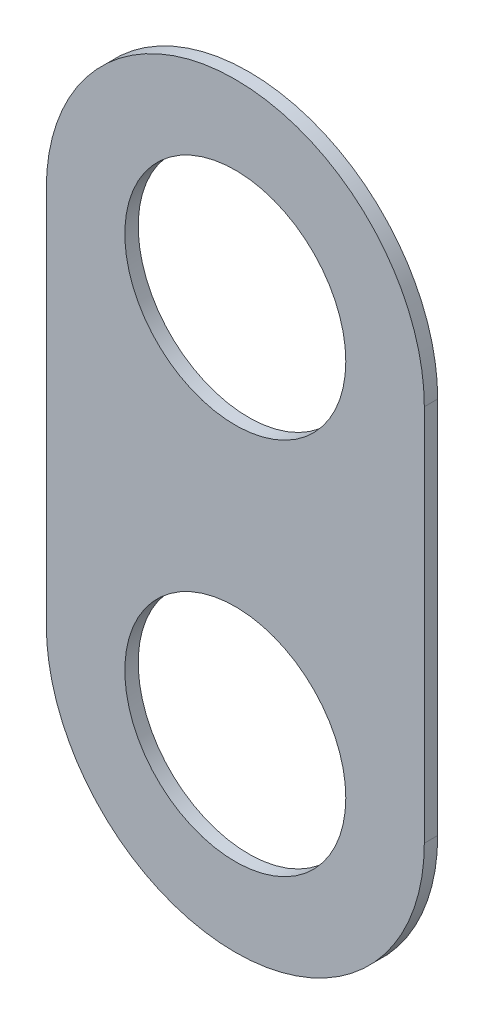
SolidWorks part; units mm, degrees
material "ASTM A36 Steel"
ref_plane "Front Plane" through (0, 0, 0) normal (0, 0, 1) x (1, 0, 0)
ref_plane "Top Plane" through (0, 0, 0) normal (0, 1, 0) x (1, 0, 0)
ref_plane "Right Plane" through (0, 0, 0) normal (1, 0, 0) x (0, 0, -1)
sketch "Sketch1" plane through (0, 0, 0) normal (0, 0, 1) x (1, 0, 0)
  line L0 (0, 24.7987) -> (0, -13.3013)
  line L1 (38.1, 24.7987) -> (38.1, -13.3013)
  arc A0 (38.1, 24.7987) -> (0, 24.7987) centre (19.05, 24.7987) ccw
  arc A1 (0, -13.3013) -> (38.1, -13.3013) centre (19.05, -13.3013) ccw
  circle A2 centre (19.05, 24.7987) radius 11.1354
  circle A3 centre (19.05, -13.3013) radius 11.1354
  point P12 (19.05, 43.8487)
  point P13 (19.05, -32.3513)
  dimension "D6" = 22.2707
  dimension "D7" = 22.2707
  dimension "D1" = 38.1
  dimension "D2" = 38.1
  dimension "D3" = 76.2
extrude "Boss-Extrude1" add sketch "Sketch1" along normal blind 1.3489
equation "\"P\"= 300'Transferred Tensile Load [lbf]"
equation "\"sigma_allow\"= 9064.86'Allowable Tensile Stress [psi] "
equation "\"E\"= 29007547.53'Elastic Modulus (ASTM A36 Steel) [psi] "
equation "\"delta_max\"= 0.005'Maximum Allowed Deflection Limit [in] "
equation "\"w_link\"= 1.50'Link Overall Width [in] "
equation "\"L_link\"= 3.0'Link Total Length [in] "
equation "\"d_hole\"= 0.8768'Pin Hole Diameter [in] "
equation "\"center_dist\"= 1.5'Hole Center-to-Center Distance [in]"
equation "\"A_net_req\"= \"P\" / \"sigma_allow\"'Required Minimum Net Cross-Sectional Area [in^2] "
equation "\"w_net\"= \"w_link\" - \"d_hole\"'Net Width Across Hole Section [in] "
equation "\"t_stress\"= \"A_net_req\" / \"w_net\"'Calculated Minimum Stress Thickness [in] "
equation "\"t_nominal\"= 0.250'Selected Nominal Plate Thickness [in] "
equation "\"A_net_act\"= ( \"w_link\" - \"d_hole\" ) * \"t_stress\"'Actual Net Cross-Sectional Area [in^2] "
equation "\"delta_act\"= ( \"P\" * \"L_link\" ) / ( \"A_net_act\" * \"E\" )'Actual Axial Extension Deflection [in] (Passes ≤0.005\" in\" ) "
equation "\"D1@Sketch1\"=\"w_link\""
equation "\"D2@Sketch1\"=\"center_dist\""
equation "\"D3@Sketch1\"=\"L_link\""
equation "\"D6@Sketch1\"=\"d_hole\""
equation "\"D7@Sketch1\"=\"d_hole\""
equation "\"D1@Boss-Extrude1\"=\"t_stress\""
